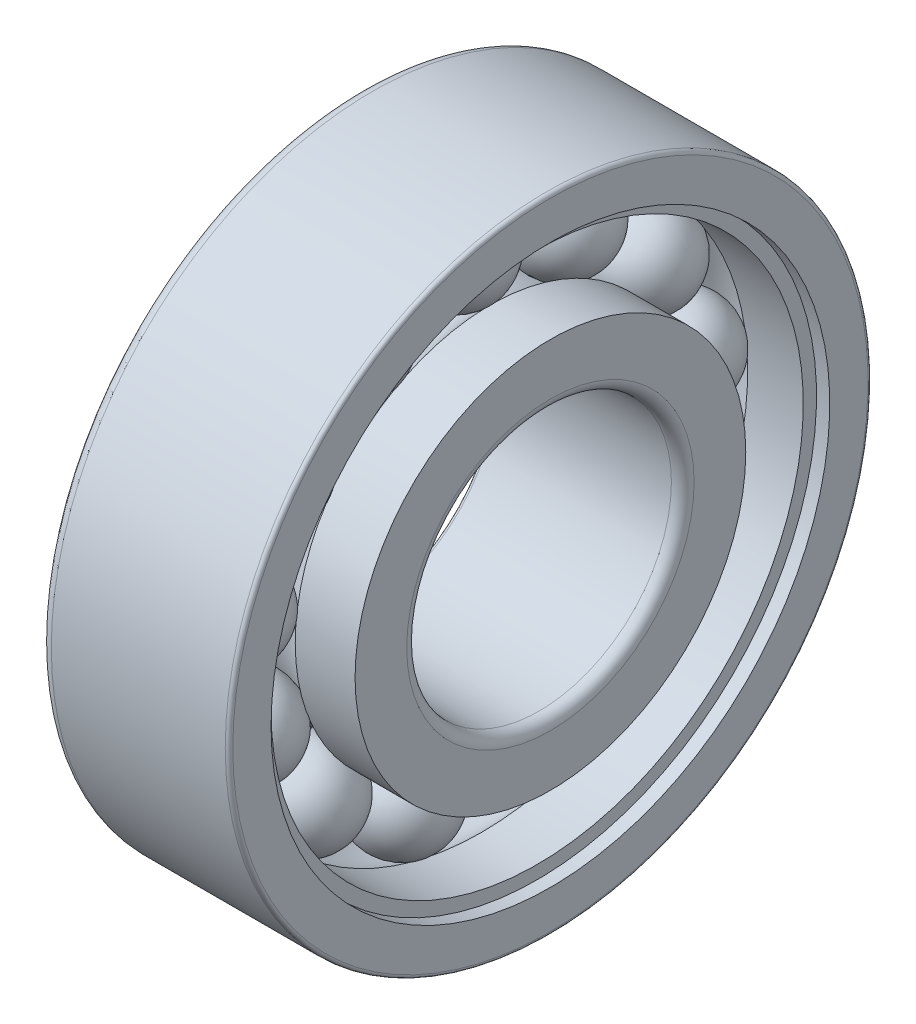
SolidWorks part; units mm, degrees
ref_plane "Front" through (0, 0, 0) normal (0, 0, 1) x (1, 0, 0)
ref_plane "Top" through (0, 0, 0) normal (0, 1, 0) x (1, 0, 0)
ref_plane "Right" through (0, 0, 0) normal (1, 0, 0) x (0, 0, -1)
other "Configuration Table"
sketch "Sketch1" plane through (0, 0, 0) normal (0, 0, 1) x (1, 0, 0)
  line L0 (-3.0919, 0) -> (2.899, 0) construction
  line L1 (-3.0919, 6) -> (2.899, 6) construction
  line L2 (-1.25, 6) -> (1.25, 6)
  arc A0 (-1.25, 6) -> (1.25, 6) centre (0, 6) ccw
  dimension "R" = 1.25
  dimension "D1" = 6
revolve "Revolve1" add sketch "Sketch1" angle 360 about L1
sketch "Sketch2" plane through (0, 0, 0) normal (0, 0, 1) x (1, 0, 0)
  line L0 (-2.5, 5.1667) -> (-0.9182, 5.1667)
  line L1 (2.5, 5.1667) -> (2.5, 3.5)
  line L2 (2.5, 3.5) -> (-2.5, 3.5)
  line L3 (-2.5, 3.5) -> (-2.5, 5.1667)
  line L4 (-2.9924, 0) -> (3.9982, 0) construction
  line L5 (-1.8743, 6) -> (3.1755, 6) construction
  line L7 (0.9182, 5.1667) -> (2.5, 5.1667)
  line L8 (-2.5, 6.2861) -> (-2.5, 1.454) construction
  arc A0 (-0.9182, 5.1667) -> (0.9182, 5.1667) centre (0, 6) ccw
  dimension "D1" = 6
  dimension "B" = 5
  dimension "D2" = 1.24
  dimension "d" = 7
  dimension "D3" = 10.3333
  dimension "T" = 5
  dimension "D6" = 2.5
revolve "Revolve2" add sketch "Sketch2" angle 360 about L4
sketch "Sketch3" plane through (0, 0, 0) normal (0, 0, 1) x (1, 0, 0)
  line L0 (-2.5, 6.8333) -> (-2.5, 8.5)
  line L1 (-2.5, 8.5) -> (2.5, 8.5)
  line L2 (2.5, 8.5) -> (2.5, 7.3883)
  line L3 (2.15, 7.0383) -> (0.6778, 7.0383)
  line L4 (-2.9924, 0) -> (3.4329, 0) construction
  line L6 (-1.7375, 6) -> (2.2712, 6) construction
  line L7 (-0.9182, 6.8333) -> (-2.5, 6.8333)
  line L8 (2.15, 7.0383) -> (2.15, 7.3883)
  line L9 (2.15, 7.3883) -> (2.5, 7.3883)
  arc A0 (0.6778, 7.0383) -> (-0.9182, 6.8333) centre (0, 6) ccw
  dimension "D1" = 6
  dimension "D4" = 1.24
  dimension "B" = 5
  dimension "DD" = 17
  dimension "D3" = 14.0767
  dimension "D5" = 13.6667
  dimension "D6" = 0.35
  dimension "D7" = 0.35
  dimension "D2" = 2.5
revolve "Revolve3" add sketch "Sketch3" angle 360 about L4
pattern_circular "Circular-Pattern1" count 13 over 360 about axis through (0, 0, 0) along (1, 0, 0) of "Revolve1"
fillet "Fillet1" radius 0.3 2 edges at (2.5, 0, 3.5) (-2.5, 0, 8.5)
fillet "Fillet2" radius 0.1 2 edges at (2.5, 0, 8.5) (-2.5, 0, 3.5)
equation "\"R@Sketch1\" =  ( \"DD@Sketch3\" - \"d@Sketch2\" )  / 8"
equation "\"D1@Sketch1\"=(\"d@Sketch2\"+\"DD@Sketch3\")/4"
equation "\"D1@Sketch2\"=(\"d@Sketch2\"+\"DD@Sketch3\")/4"
equation "\"D3@Sketch2\" =  \"d@Sketch2\"+  ( \"DD@Sketch3\" - \"d@Sketch2\" )  /3"
equation "\"D2@Sketch2\" =  ( \"DD@Sketch3\" - \"d@Sketch2\" )  / 8 - 0.01"
equation "\"D6@Sketch2\" = \"B@Sketch2\" / 2"
equation "\"B@Sketch3\" = \"B@Sketch2\""
equation "\"D2@Sketch3\" = \"B@Sketch3\" / 2"
equation "\"D1@Sketch3\"=(\"d@Sketch2\"+\"DD@Sketch3\")/4"
equation "\"D3@Sketch3\" = (  \"DD@Sketch3\" -  (\"DD@Sketch3\" - \"d@Sketch2\"  )  / 3 )  * 1.03"
equation "\"D5@Sketch3\" = \"DD@Sketch3\" -  (  \"DD@Sketch3\" - \"d@Sketch2\")  / 3"
equation "\"D6@Sketch3\" = \"d@Sketch2\" / 20"
equation "\"D7@Sketch3\"=\"D6@Sketch3\""
equation "\"D4@Sketch3\"=(\"DD@Sketch3\"-\"d@Sketch2\")/8-0.01"
equation "\"m@Circular-Pattern1\" = int( 3.14159265 / atn(\"R@Sketch1\" / sqr((\"d@Sketch2\"+\"DD@Sketch3\")/4 * (\"d@Sketch2\"+\"DD@Sketch3\")/4 - \"R@Sketch1\" *  \"R@Sketch1\")))-1"
